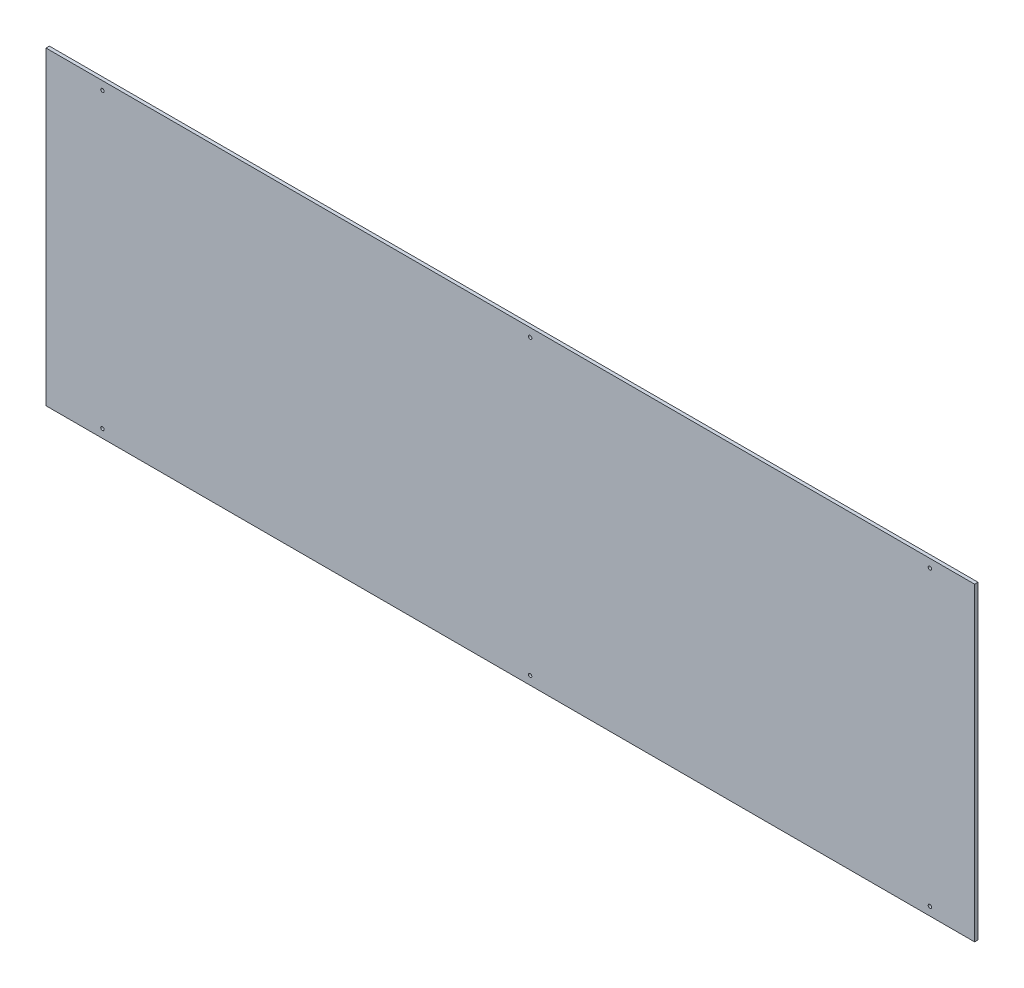
SolidWorks part; units mm, degrees
ref_plane "前视基准面" through (0, 0, 0) normal (0, 0, 1) x (1, 0, 0)
ref_plane "上视基准面" through (0, 0, 0) normal (0, 1, 0) x (1, 0, 0)
ref_plane "右视基准面" through (0, 0, 0) normal (1, 0, 0) x (0, 0, -1)
sketch "草图1" plane through (0, 0, 0) normal (0, 0, 1) x (1, 0, 0)
  line L1 (-51.8699, 328.3598) -> (1048.1301, 328.3598)
  line L2 (-51.8699, 328.3598) -> (-51.8699, -38.6402)
  line L3 (-51.8699, -38.6402) -> (1048.1301, -38.6402)
  line L4 (1048.1301, 328.3598) -> (1048.1301, -38.6402)
  dimension "D1" = 367
  dimension "D2" = 1100
extrude "凸台-拉伸1" add sketch "草图1" along normal blind 4
sketch "草图2" plane through (0, 0, 4) normal (0, 0, 1) x (1, 0, 0)
  circle A0 centre (14.9565, 318.3598) radius 2
  circle A1 centre (521.6293, 318.3598) radius 2
  circle A2 centre (995.1345, 318.3598) radius 2
  circle A3 centre (995.1345, -28.6402) radius 2
  circle A4 centre (521.6293, -28.6402) radius 2
  circle A5 centre (14.9565, -28.6402) radius 2
  dimension "D1" = 4
  dimension "D2" = 4
  dimension "D3" = 4
  dimension "D4" = 4
  dimension "D5" = 4
  dimension "D6" = 4
extrude "切除-拉伸1" cut sketch "草图2" against normal blind 4
